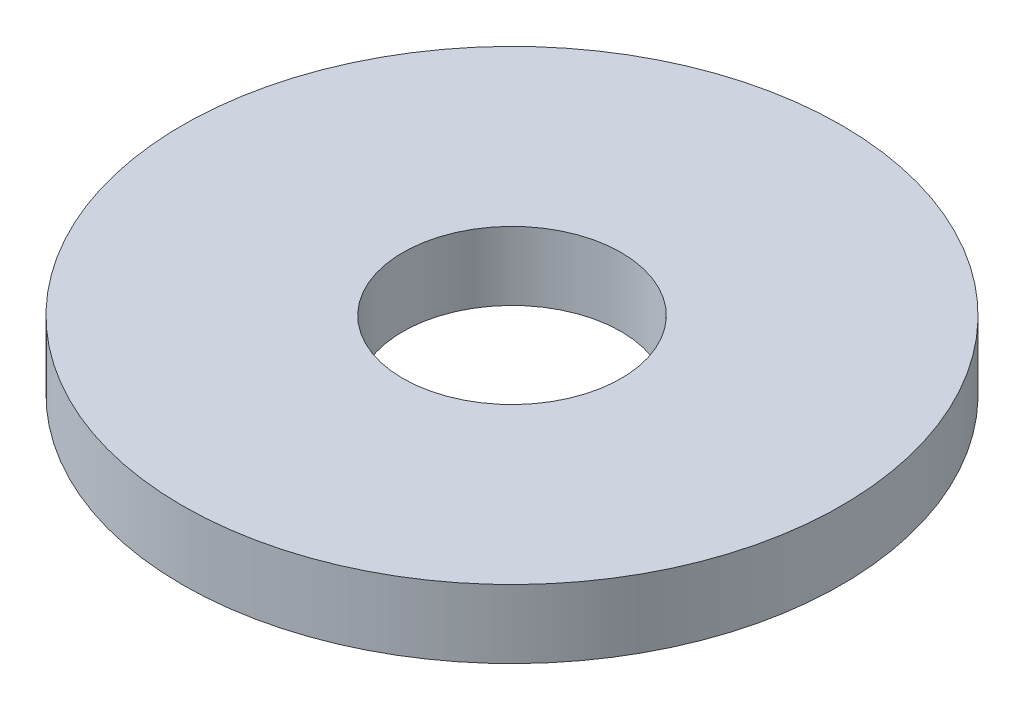
SolidWorks part; units mm, degrees
ref_plane "Alzado" through (0, 0, 0) normal (0, 0, 1) x (1, 0, 0)
ref_plane "Planta" through (0, 0, 0) normal (0, 1, 0) x (1, 0, 0)
ref_plane "Vista lateral" through (0, 0, 0) normal (1, 0, 0) x (0, 0, -1)
sketch "Croquis2" plane through (0, 0, 0) normal (0, 1, 0) x (1, 0, 0)
  circle A0 centre (0, 0) radius 3.2385
  circle A1 centre (0, 0) radius 9.779
  dimension "D1" = 6.477
  dimension "D2" = 19.558
extrude "Saliente-Extruir1" add sketch "Croquis2" along normal blind 2.032
